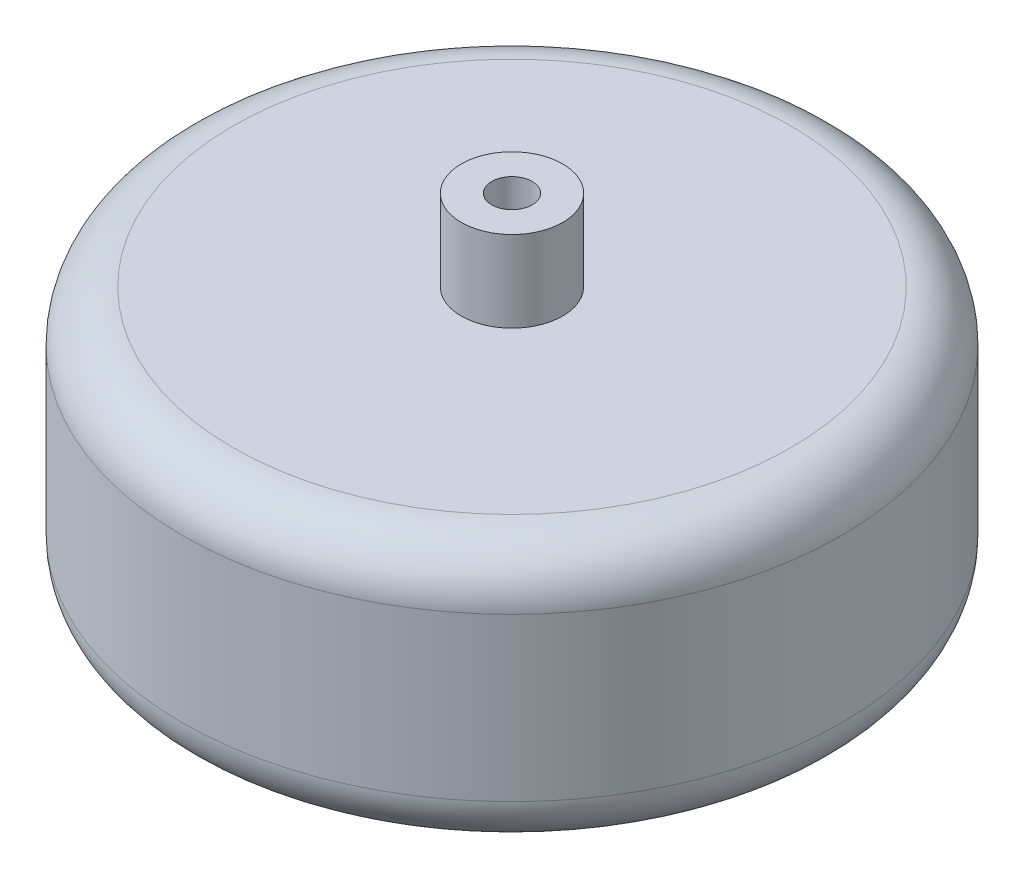
SolidWorks part; units mm, degrees
ref_plane "Front Plane" through (0, 0, 0) normal (0, 0, 1) x (1, 0, 0)
ref_plane "Top Plane" through (0, 0, 0) normal (0, 1, 0) x (1, 0, 0)
ref_plane "Right Plane" through (0, 0, 0) normal (1, 0, 0) x (0, 0, -1)
sketch "Sketch1" plane through (0, 0, 0) normal (0, 1, 0) x (1, 0, 0)
  circle A0 centre (0, 0) radius 32.5
  dimension "D1" = 65
extrude "Boss-Extrude1" add sketch "Sketch1" along normal blind 26
sketch "Sketch2" plane through (0, 26, 0) normal (0, 1, 0) x (1, 0, 0)
  circle A0 centre (0, 0) radius 5
  dimension "D1" = 10
extrude "Boss-Extrude2" add sketch "Sketch2" along normal blind 8
sketch "Sketch3" plane through (0, 34, 0) normal (0, 1, 0) x (1, 0, 0)
  circle A0 centre (0, 0) radius 2
  dimension "D1" = 4
extrude "Cut-Extrude1" cut sketch "Sketch3" against normal blind 8
fillet "Fillet1" radius 5 2 edges at (0, 0, 32.5) (0, 26, 32.5)
